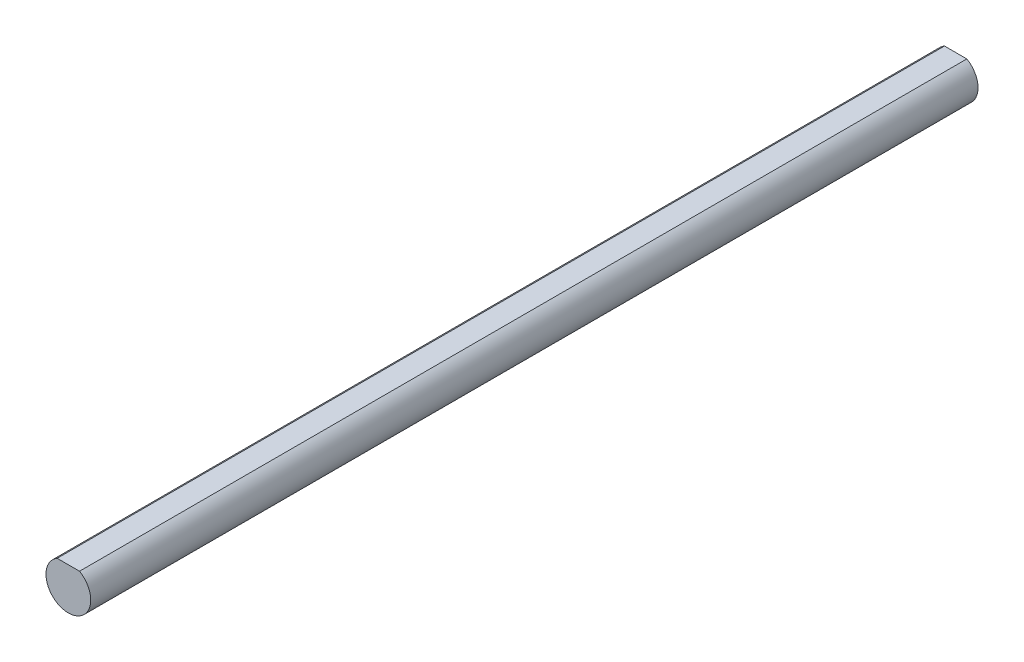
SolidWorks part; units mm, degrees
ref_plane "Front Plane" through (0, 0, 0) normal (0, 0, 1) x (1, 0, 0)
ref_plane "Top Plane" through (0, 0, 0) normal (0, 1, 0) x (1, 0, 0)
ref_plane "Right Plane" through (0, 0, 0) normal (1, 0, 0) x (0, 0, -1)
sketch "Sketch2" plane through (0, 0, 0) normal (0, 0, 1) x (1, 0, 0)
  line L0 (-1.5, 2.5981) -> (1.5, 2.5981)
  arc A0 (-1.5, 2.5981) -> (1.5, 2.5981) centre (0, 0) ccw
  dimension "D1" = 6
  dimension "D2" = 3
extrude "Boss-Extrude1" add sketch "Sketch2" along normal blind 119
